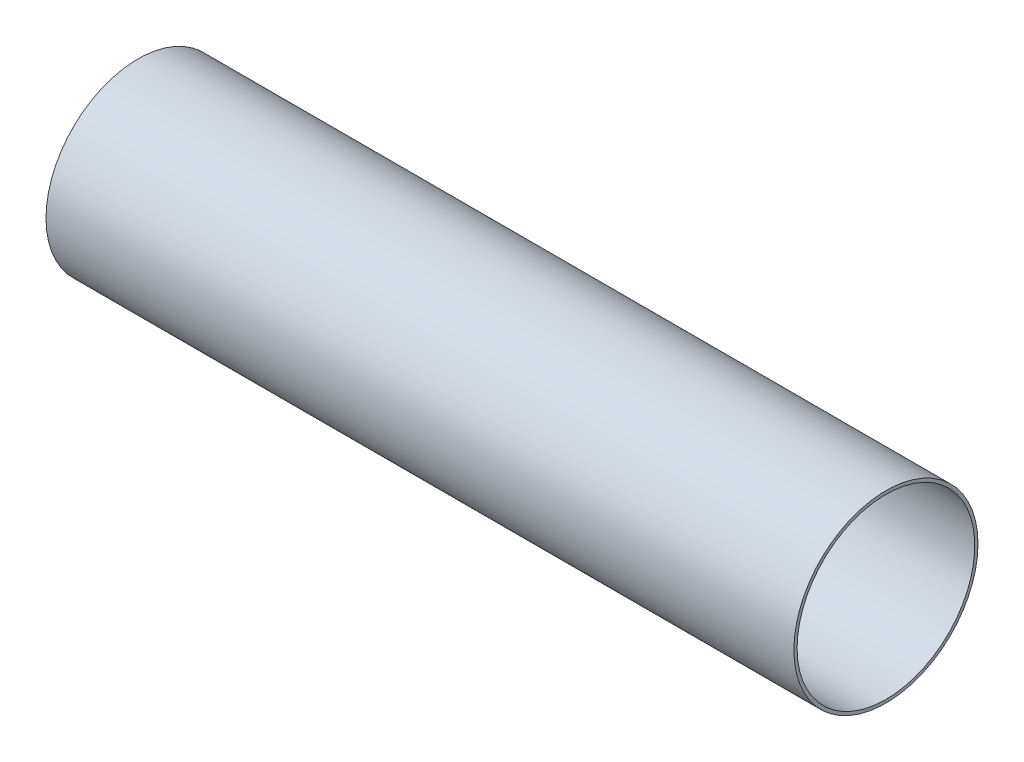
SolidWorks part; units mm, degrees
ref_plane "Front Plane" through (0, 0, 0) normal (0, 0, 1) x (1, 0, 0)
ref_plane "Top Plane" through (0, 0, 0) normal (0, 1, 0) x (1, 0, 0)
ref_plane "Right Plane" through (0, 0, 0) normal (1, 0, 0) x (0, 0, -1)
sketch "Sketch3" plane through (0, 0, 0) normal (0, 0, 1) x (1, 0, 0)
  line L0 (0, 0) -> (423.5652, 0) construction
  line L1 (0, 57) -> (463, 57)
  line L2 (0, 57) -> (0, 55)
  line L3 (0, 55) -> (463, 55)
  line L4 (463, 57) -> (463, 55)
  dimension "D1" = 2
  dimension "D2" = 55
  dimension "D3" = 463
revolve "Revolve1" add sketch "Sketch3" angle 360 about L0
